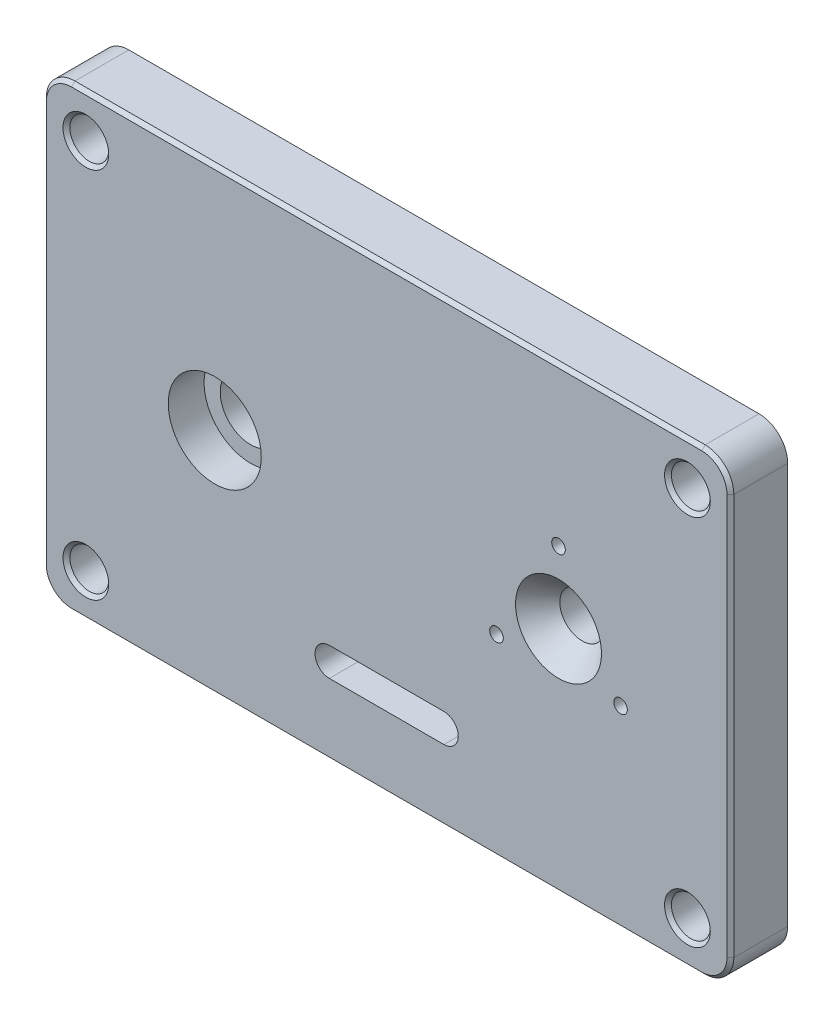
SolidWorks part; units mm, degrees
ref_plane "前视基准面" through (0, 0, 0) normal (0, 0, 1) x (1, 0, 0)
ref_plane "上视基准面" through (0, 0, 0) normal (0, 1, 0) x (1, 0, 0)
ref_plane "右视基准面" through (0, 0, 0) normal (1, 0, 0) x (0, 0, -1)
sketch "草图1" plane through (0, 0, 0) normal (0, 0, 1) x (1, 0, 0)
  line L0 (6.35, 0) -> (146.05, 0)
  line L1 (152.4, 6.35) -> (152.4, 95.25)
  line L2 (146.05, 101.6) -> (6.35, 101.6)
  line L3 (0, 95.25) -> (0, 6.35)
  arc A0 (0, 6.35) -> (6.35, 0) centre (6.35, 6.35) ccw
  arc A1 (146.05, 0) -> (152.4, 6.35) centre (146.05, 6.35) ccw
  arc A2 (152.4, 95.25) -> (146.05, 101.6) centre (146.05, 95.25) ccw
  arc A3 (6.35, 101.6) -> (0, 95.25) centre (6.35, 95.25) ccw
extrude "凸台-拉伸1" add sketch "草图1" along normal blind 12.7
ref_plane "基准面1" through (0, 0, 12.7) normal (0, 0, 1) x (1, 0, 0)
sketch "草图2" plane through (0, 0, 12.7) normal (0, 0, 1) x (1, 0, 0)
  circle A0 centre (9.525, 9.525) radius 4.3053
  circle A1 centre (142.875, 9.525) radius 4.3053
  circle A2 centre (9.525, 92.075) radius 4.3053
  circle A3 centre (142.875, 92.075) radius 4.3053
extrude "切除-拉伸1" cut sketch "草图2" against normal through all
sketch "草图3" plane through (0, 0, 12.7) normal (0, 0, 1) x (1, 0, 0)
  line L0 (63.5, 15.875) -> (88.9, 15.875)
  line L1 (88.9, 22.225) -> (63.5, 22.225)
  arc A0 (88.9, 15.875) -> (88.9, 22.225) centre (88.9, 19.05) ccw
  arc A1 (63.5, 22.225) -> (63.5, 15.875) centre (63.5, 19.05) ccw
extrude "切除-拉伸2" cut sketch "草图3" against normal through all
sketch "草图4" plane through (0, 0, 12.7) normal (0, 0, 1) x (1, 0, 0)
  circle A0 centre (38.1, 50.8) radius 10.3124
extrude "切除-拉伸3" cut sketch "草图4" against normal blind 7.9502
sketch "草图5" plane through (0, 0, 12.7) normal (0, 0, 1) x (1, 0, 0)
  circle A0 centre (38.1, 50.8) radius 6.7437
extrude "切除-拉伸4" cut sketch "草图5" against normal through all
sketch "草图6" plane through (0, 0, 12.7) normal (0, 0, 1) x (1, 0, 0)
  circle A0 centre (114.3, 50.8) radius 9.525
extrude "切除-拉伸5" cut sketch "草图6" against normal blind 5.2449 draft 41
sketch "草图7" plane through (0, 0, 12.7) normal (0, 0, 1) x (1, 0, 0)
  circle A0 centre (114.3, 50.8) radius 4.9657
extrude "切除-拉伸6" cut sketch "草图7" against normal through all
sketch "草图8" plane through (0, 0, 12.7) normal (0, 0, 1) x (1, 0, 0)
  circle A0 centre (114.3, 66.675) radius 1.505
  circle A1 centre (100.5518, 42.8625) radius 1.505
  circle A2 centre (128.0482, 42.8625) radius 1.505
extrude "切除-拉伸7" cut sketch "草图8" against normal blind 9.525
ref_plane "基准面2" through (0, 0, 3.175) normal (0, 0, 1) x (1, 0, 0)
sketch "草图9" plane through (0, 0, 3.175) normal (0, 0, 1) x (1, 0, 0)
  circle A0 centre (114.3, 66.675) radius 1.505
  circle A1 centre (100.5518, 42.8625) radius 1.505
  circle A2 centre (128.0482, 42.8625) radius 1.505
extrude "切除-拉伸8" cut sketch "草图9" against normal blind 0.9013 draft 59
chamfer "倒角1" distance 0.762 angle 45 8 edges at (152.4, 50.8, 12.7) (0, 50.8, 12.7) (76.2, 101.6, 12.7) (1.8599, 99.7401, 12.7) (150.5401, 99.7401, 12.7) (1.8599, 1.8599, 12.7) (150.5401, 1.8599, 12.7) (76.2, 0, 12.7)
chamfer "倒角2" distance 0.762 angle 45 4 edges at (147.1803, 92.075, 12.7) (13.8303, 92.075, 12.7) (147.1803, 9.525, 12.7) (13.8303, 9.525, 12.7)
